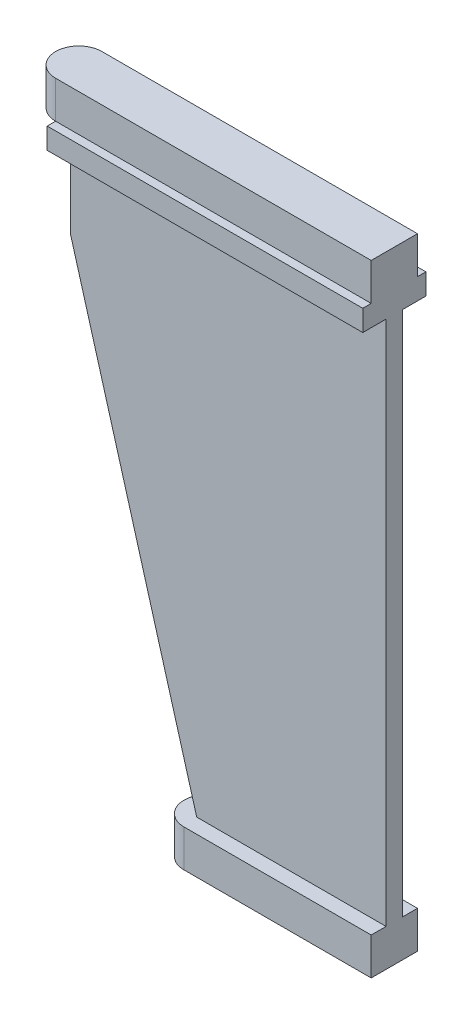
SolidWorks part; units mm, degrees
ref_plane "Front Plane" through (0, 0, 0) normal (0, 0, 1) x (1, 0, 0)
ref_plane "Top Plane" through (0, 0, 0) normal (0, 1, 0) x (1, 0, 0)
ref_plane "Right Plane" through (0, 0, 0) normal (1, 0, 0) x (0, 0, -1)
sketch "Sketch1" plane through (0, 0, 0) normal (0, 0, 1) x (1, 0, 0)
  line L0 (0, 0) -> (-22.86, 0)
  line L1 (-22.86, 0) -> (-38.1, 53.34)
  line L2 (-38.1, 53.34) -> (-38.1, 66.04)
  line L3 (0, 66.04) -> (0, 0)
  line L4 (-38.1, 66.04) -> (0, 66.04)
  dimension "D1" = 66.04
  dimension "D2" = 38.1
  dimension "D3" = 12.7
  dimension "D4" = 22.86
extrude "Boss-Extrude1" add sketch "Sketch1" along normal blind 2
sketch "Sketch2" plane through (0, 0, 0) normal (0, -1, 0) x (1, 0, 0)
  line L0 (0, 1) -> (-22.86, 1) construction
  line L1 (0, 2) -> (0, 0) construction
  line L2 (-22.86, 2) -> (-22.86, 0) construction
  line L3 (0, 1) -> (-22.606, 1) construction
  line L4 (0, -1.794) -> (-22.606, -1.794)
  line L5 (0, 3.794) -> (-22.606, 3.794)
  line L6 (0, 3.794) -> (0, -1.794)
  arc A1 (-22.606, 3.794) -> (-22.606, -1.794) centre (-22.606, 1) ccw
  point P6 (-3.4368, 0.5)
  dimension "D1" = 2.794
  dimension "D2" = 25.4
extrude "Boss-Extrude2" add sketch "Sketch2" along normal blind 4.4958
sketch "Sketch3" plane through (0, 66.04, 0) normal (0, 1, 0) x (1, 0, 0)
  line L0 (0, -1) -> (-38.1, -1) construction
  line L1 (0, -2) -> (0, 0) construction
  line L2 (-38.1, -2) -> (-38.1, 0) construction
  line L3 (0, 1.794) -> (0, -3.794)
  line L4 (0, 1.794) -> (-38.1, 1.794)
  line L5 (-38.1, -3.794) -> (0, -3.794)
  arc A0 (-38.1, 1.794) -> (-38.1, -3.794) centre (-38.1, -1) ccw
  arc A1 (-22.606, 1.794) -> (-22.606, -3.794) centre (-22.606, -1) ccw construction
extrude "Boss-Extrude3" add sketch "Sketch3" along normal blind 4.4958
sketch "Sketch4" plane through (0, 66.04, 0) normal (0, -1, 0) x (1, 0, 0)
  line L0 (-40.894, 1) -> (-38.1, 1) construction
  line L1 (0, 4.81) -> (-38.1, 4.81)
  line L2 (0, 4.81) -> (0, -2.81)
  line L3 (0, -2.81) -> (-38.1, -2.81)
  line L4 (-38.1, 4.81) -> (-38.1, -2.81)
  line L5 (0, -1.794) -> (0, 3.794) construction
  line L6 (-38.1, 2) -> (-38.1, 0) construction
  arc A0 (-38.1, 3.794) -> (-38.1, -1.794) centre (-38.1, 1) ccw construction
  dimension "D1" = 7.62
extrude "Boss-Extrude4" add sketch "Sketch4" along normal blind 2.54
sketch "Sketch5" plane through (0, 0, 0) normal (0, 1, 0) x (1, 0, 0)
  line L0 (-38.1, 2.81) -> (0, 2.81) construction
  line L1 (0, -4.81) -> (-22.86, -4.81)
  line L2 (0, -4.81) -> (0, 2.81)
  line L3 (0, 2.81) -> (-22.86, 2.81)
  line L4 (-22.86, -4.81) -> (-22.86, 2.81)
  line L5 (-22.86, -2) -> (-22.86, 0) construction
